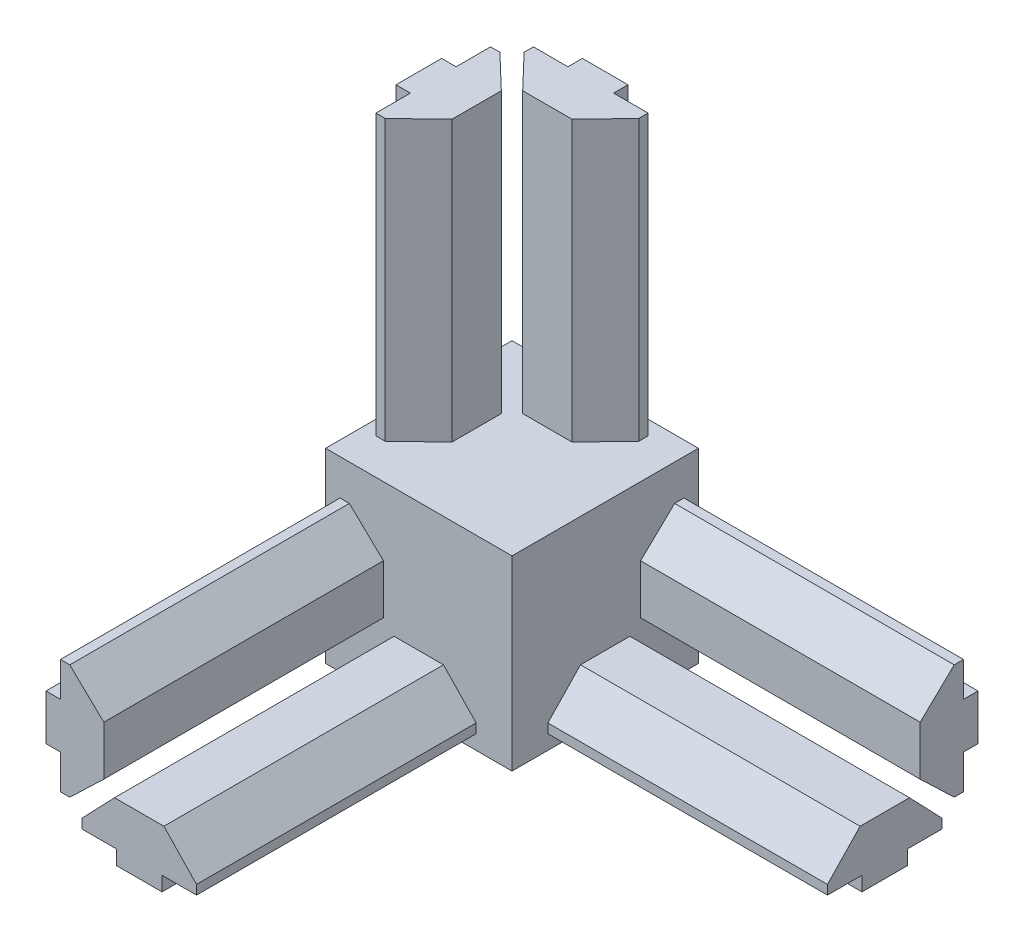
SolidWorks part; units mm, degrees
ref_plane "Plan de face" through (0, 0, 0) normal (0, 0, 1) x (1, 0, 0)
ref_plane "Plan de dessus" through (0, 0, 0) normal (0, 1, 0) x (1, 0, 0)
ref_plane "Plan de droite" through (0, 0, 0) normal (1, 0, 0) x (0, 0, -1)
sketch "Esquisse1" plane through (0, 0, 0) normal (0, 0, 1) x (1, 0, 0)
  line L0 (-48.9124, 21.2323) -> (-28.9124, 21.2323)
  line L1 (-28.9124, 21.2323) -> (-28.9124, 1.2323)
  line L2 (-48.9124, 21.2323) -> (-48.9124, 1.2323)
  line L3 (-48.9124, 1.2323) -> (-28.9124, 1.2323)
extrude "Boss.-Extru.1" add sketch "Esquisse1" along normal blind 20
sketch "Esquisse2" plane through (0, 0, 20) normal (0, 0, 1) x (1, 0, 0)
  line L0 (-41.3624, 1.2323) -> (-41.3624, 2.7823)
  line L1 (-48.9124, 1.2323) -> (-28.9124, 1.2323) construction
  line L2 (-41.3624, 2.7823) -> (-45.0624, 2.7823)
  line L3 (-45.0624, 2.7823) -> (-45.0624, 3.7823)
  line L4 (-45.0624, 3.7823) -> (-41.5624, 7.4365)
  line L5 (-41.5624, 7.4365) -> (-36.2624, 7.4365)
  line L6 (-36.2624, 7.4365) -> (-32.7624, 3.7823)
  line L7 (-32.7624, 3.7823) -> (-32.7624, 2.7823)
  line L8 (-32.7624, 2.7823) -> (-36.4624, 2.7823)
  line L9 (-36.4624, 2.7823) -> (-36.4624, 1.2323)
  line L14 (-48.9124, 21.2323) -> (-48.9124, 1.2323)
  line L15 (-48.9124, 1.2323) -> (-28.9124, 1.2323)
  line L16 (-28.9124, 1.2323) -> (-28.9124, 21.2323)
  line L17 (-28.9124, 21.2323) -> (-48.9124, 21.2323)
  line L19 (-41.3624, 1.2323) -> (-36.4624, 1.2323)
  dimension "D1" = 7.55
  dimension "D2" = 1.55
  dimension "D3" = 3.7
  dimension "D4" = 1
  dimension "D5" = 5.06
  dimension "D6" = 5.3
  dimension "D7" = 5.06
  dimension "D8" = 1
  dimension "D9" = 3.7
  dimension "D10" = 1.55
  dimension "D11" = 7.55
  dimension "D12" = 0
extrude "Boss.-Extru.2" add sketch "Esquisse2" along normal blind 30
sketch "Esquisse3" plane through (-28.9124, 0, 0) normal (1, 0, 0) x (0, 0, -1)
  line L0 (0, 8.7823) -> (-1.55, 8.7823)
  line L1 (0, 1.2323) -> (0, 21.2323) construction
  line L2 (-1.55, 8.7823) -> (-1.55, 5.0823)
  line L3 (-1.55, 5.0823) -> (-2.55, 5.0823)
  line L4 (-2.55, 5.0823) -> (-6.2043, 8.5823)
  line L5 (-6.2043, 8.5823) -> (-6.2043, 13.8823)
  line L6 (-6.2043, 13.8823) -> (-2.55, 17.3823)
  line L7 (-2.55, 17.3823) -> (-1.55, 17.3823)
  line L8 (-1.55, 17.3823) -> (-1.55, 13.6823)
  line L9 (-1.55, 13.6823) -> (0, 13.6823)
  line L14 (0, 1.2323) -> (0, 21.2323)
  line L15 (0, 21.2323) -> (-20, 21.2323)
  line L16 (-20, 21.2323) -> (-20, 1.2323)
  line L17 (-20, 1.2323) -> (0, 1.2323)
  line L18 (0, 8.7823) -> (0, 13.6823)
  dimension "D1" = 7.55
  dimension "D2" = 1.55
  dimension "D3" = 3.7
  dimension "D4" = 1
  dimension "D5" = 5.06
  dimension "D6" = 5.3
  dimension "D7" = 5.06
  dimension "D8" = 1
  dimension "D9" = 3.7
  dimension "D10" = 7.55
  dimension "D11" = 0
extrude "Boss.-Extru.3" add sketch "Esquisse3" along normal blind 30
sketch "Esquisse4" plane through (0, 21.2323, 0) normal (0, 1, 0) x (1, 0, 0)
  line L0 (-36.4624, 0) -> (-36.4624, -1.55)
  line L1 (-28.9124, 0) -> (-48.9124, 0) construction
  line L2 (-36.4624, -1.55) -> (-32.7624, -1.55)
  line L3 (-32.7624, -1.55) -> (-32.7624, -2.55)
  line L4 (-32.7624, -2.55) -> (-36.2624, -6.2043)
  line L5 (-36.2624, -6.2043) -> (-41.5624, -6.2043)
  line L6 (-41.5624, -6.2043) -> (-45.0624, -2.55)
  line L7 (-45.0624, -2.55) -> (-45.0624, -1.55)
  line L8 (-45.0624, -1.55) -> (-41.3624, -1.55)
  line L9 (-41.3624, -1.55) -> (-41.3624, 0)
  line L14 (-28.9124, 0) -> (-48.9124, 0)
  line L15 (-48.9124, 0) -> (-48.9124, -20)
  line L16 (-48.9124, -20) -> (-28.9124, -20)
  line L17 (-28.9124, -20) -> (-28.9124, 0)
  line L18 (-36.4624, 0) -> (-41.3624, 0)
  dimension "D1" = 7.55
  dimension "D2" = 1.55
  dimension "D3" = 3.7
  dimension "D4" = 1
  dimension "D5" = 5.06
  dimension "D6" = 5.3
  dimension "D7" = 5.06
  dimension "D8" = 1
  dimension "D9" = 3.7
  dimension "D10" = 1.55
  dimension "D11" = 7.55
  dimension "D12" = 0
extrude "Boss.-Extru.4" add sketch "Esquisse4" along normal blind 30
sketch "Esquisse6" plane through (-28.9124, 0, 0) normal (1, 0, 0) x (0, 0, -1)
  line L0 (-12.45, 1.2323) -> (-12.45, 2.7823)
  line L1 (-20, 1.2323) -> (0, 1.2323) construction
  line L2 (-12.45, 2.7823) -> (-16.15, 2.7823)
  line L3 (-16.15, 2.7823) -> (-16.15, 3.7823)
  line L4 (-16.15, 3.7823) -> (-12.65, 7.4365)
  line L5 (-12.65, 7.4365) -> (-7.35, 7.4365)
  line L6 (-7.35, 7.4365) -> (-3.85, 3.7823)
  line L7 (-3.85, 3.7823) -> (-3.85, 2.7823)
  line L8 (-3.85, 2.7823) -> (-7.55, 2.7823)
  line L9 (-7.55, 2.7823) -> (-7.55, 1.2323)
  line L24 (0, 8.7823) -> (-1.55, 8.7823)
  line L25 (-1.55, 8.7823) -> (-1.55, 5.0823)
  line L26 (-1.55, 5.0823) -> (-2.55, 5.0823)
  line L27 (-2.55, 5.0823) -> (-6.2043, 8.5823)
  line L28 (-6.2043, 8.5823) -> (-6.2043, 13.8823)
  line L29 (-6.2043, 13.8823) -> (-2.55, 17.3823)
  line L30 (-2.55, 17.3823) -> (-1.55, 17.3823)
  line L31 (-1.55, 17.3823) -> (-1.55, 13.6823)
  line L32 (-1.55, 13.6823) -> (0, 13.6823)
  line L33 (0, 13.6823) -> (0, 21.2323)
  line L34 (0, 21.2323) -> (-20, 21.2323)
  line L35 (-20, 21.2323) -> (-20, 1.2323)
  line L36 (-20, 1.2323) -> (0, 1.2323)
  line L37 (0, 1.2323) -> (0, 8.7823)
  line L50 (-12.45, 1.2323) -> (-7.55, 1.2323)
  dimension "D1" = 7.55
  dimension "D2" = 1.55
  dimension "D3" = 3.7
  dimension "D4" = 1
  dimension "D5" = 5.06
  dimension "D6" = 5.3
  dimension "D7" = 5.06
  dimension "D8" = 1
  dimension "D9" = 3.7
  dimension "D10" = 1.55
  dimension "D11" = 7.55
  dimension "D12" = 0
extrude "Boss.-Extru.5" add sketch "Esquisse6" along normal blind 30
sketch "Esquisse8" plane through (0, 21.2323, 0) normal (0, 1, 0) x (1, 0, 0)
  line L0 (-48.9124, -7.55) -> (-47.3624, -7.55)
  line L1 (-48.9124, -20) -> (-48.9124, 0) construction
  line L2 (-47.3624, -7.55) -> (-47.3624, -3.85)
  line L3 (-47.3624, -3.85) -> (-46.3624, -3.85)
  line L4 (-46.3624, -3.85) -> (-42.7081, -7.35)
  line L5 (-42.7081, -7.35) -> (-42.7081, -12.65)
  line L6 (-42.7081, -12.65) -> (-46.3624, -16.15)
  line L7 (-46.3624, -16.15) -> (-47.3624, -16.15)
  line L8 (-47.3624, -16.15) -> (-47.3624, -12.45)
  line L9 (-47.3624, -12.45) -> (-48.9124, -12.45)
  line L24 (-36.4624, 0) -> (-36.4624, -1.55)
  line L25 (-36.4624, -1.55) -> (-32.7624, -1.55)
  line L26 (-32.7624, -1.55) -> (-32.7624, -2.55)
  line L27 (-32.7624, -2.55) -> (-36.2624, -6.2043)
  line L28 (-36.2624, -6.2043) -> (-41.5624, -6.2043)
  line L29 (-41.5624, -6.2043) -> (-45.0624, -2.55)
  line L30 (-45.0624, -2.55) -> (-45.0624, -1.55)
  line L31 (-45.0624, -1.55) -> (-41.3624, -1.55)
  line L32 (-41.3624, -1.55) -> (-41.3624, 0)
  line L33 (-41.3624, 0) -> (-48.9124, 0)
  line L34 (-48.9124, 0) -> (-48.9124, -20)
  line L35 (-48.9124, -20) -> (-28.9124, -20)
  line L36 (-28.9124, -20) -> (-28.9124, 0)
  line L37 (-28.9124, 0) -> (-36.4624, 0)
  line L48 (-48.9124, -7.55) -> (-48.9124, -12.45)
  dimension "D1" = 7.55
  dimension "D2" = 1.55
  dimension "D3" = 3.7
  dimension "D4" = 1
  dimension "D5" = 5.06
  dimension "D6" = 5.3
  dimension "D7" = 5.06
  dimension "D8" = 1
  dimension "D9" = 3.7
  dimension "D10" = 1.55
  dimension "D11" = 7.55
  dimension "D12" = 0
extrude "Boss.-Extru.6" add sketch "Esquisse8" along normal blind 30
sketch "Esquisse9" plane through (0, 0, 20) normal (0, 0, 1) x (1, 0, 0)
  line L0 (-48.9124, 13.6823) -> (-47.3624, 13.6823)
  line L1 (-48.9124, 21.2323) -> (-48.9124, 1.2323) construction
  line L2 (-47.3624, 13.6823) -> (-47.3624, 17.3823)
  line L3 (-47.3624, 17.3823) -> (-46.3624, 17.3823)
  line L4 (-46.3624, 17.3823) -> (-42.7081, 13.8823)
  line L5 (-42.7081, 13.8823) -> (-42.7081, 8.5823)
  line L6 (-42.7081, 8.5823) -> (-46.3624, 5.0823)
  line L7 (-46.3624, 5.0823) -> (-47.3624, 5.0823)
  line L8 (-47.3624, 5.0823) -> (-47.3624, 8.7823)
  line L9 (-47.3624, 8.7823) -> (-48.9124, 8.7823)
  line L24 (-41.3624, 1.2323) -> (-41.3624, 2.7823)
  line L25 (-41.3624, 2.7823) -> (-45.0624, 2.7823)
  line L26 (-45.0624, 2.7823) -> (-45.0624, 3.7823)
  line L27 (-45.0624, 3.7823) -> (-41.5624, 7.4365)
  line L28 (-41.5624, 7.4365) -> (-36.2624, 7.4365)
  line L29 (-36.2624, 7.4365) -> (-32.7624, 3.7823)
  line L30 (-32.7624, 3.7823) -> (-32.7624, 2.7823)
  line L31 (-32.7624, 2.7823) -> (-36.4624, 2.7823)
  line L32 (-36.4624, 2.7823) -> (-36.4624, 1.2323)
  line L33 (-36.4624, 1.2323) -> (-28.9124, 1.2323)
  line L34 (-28.9124, 1.2323) -> (-28.9124, 21.2323)
  line L35 (-28.9124, 21.2323) -> (-48.9124, 21.2323)
  line L36 (-48.9124, 21.2323) -> (-48.9124, 1.2323)
  line L37 (-48.9124, 1.2323) -> (-41.3624, 1.2323)
  line L50 (-48.9124, 13.6823) -> (-48.9124, 8.7823)
  dimension "D1" = 7.55
  dimension "D2" = 1.55
  dimension "D3" = 3.7
  dimension "D4" = 1
  dimension "D5" = 5.06
  dimension "D6" = 5.3
  dimension "D7" = 5.06
  dimension "D8" = 1
  dimension "D9" = 3.7
  dimension "D10" = 1.55
  dimension "D11" = 7.55
  dimension "D12" = 0
extrude "Boss.-Extru.7" add sketch "Esquisse9" along normal blind 30
